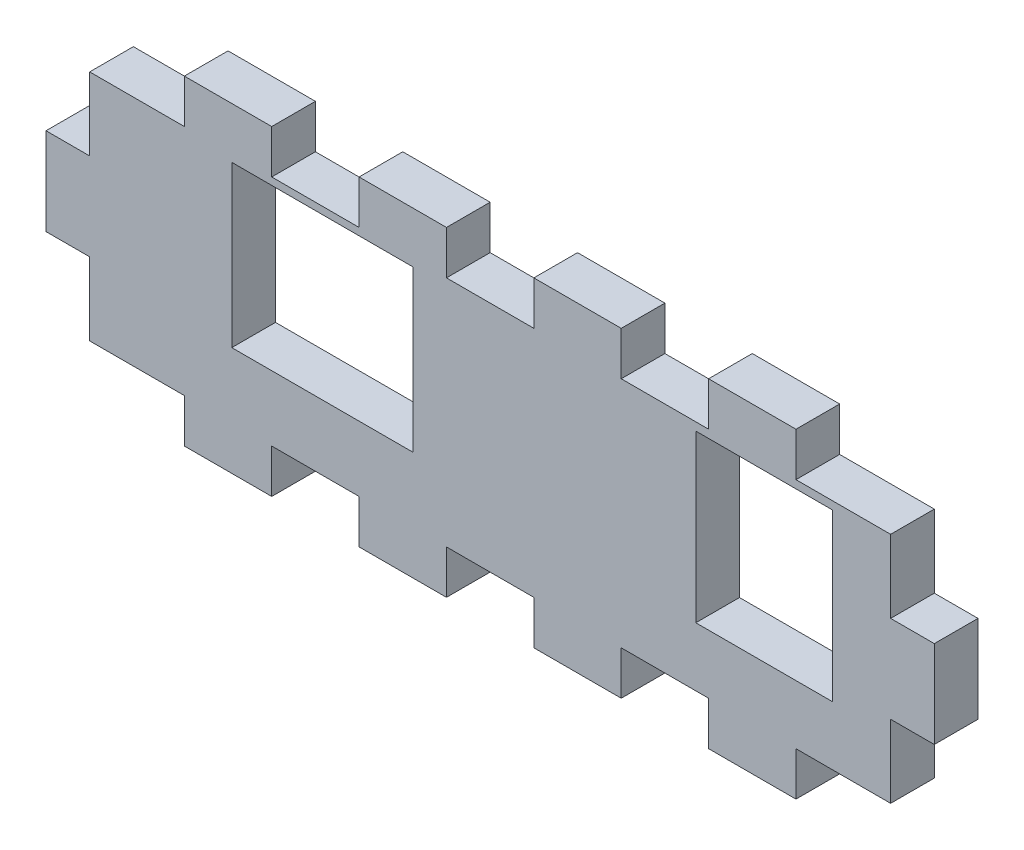
SolidWorks part; units mm, degrees
material "PMMA"
ref_plane "前视基准面" through (0, 0, 0) normal (0, 0, 1) x (1, 0, 0)
ref_plane "上视基准面" through (0, 0, 0) normal (0, 1, 0) x (1, 0, 0)
ref_plane "右视基准面" through (0, 0, 0) normal (1, 0, 0) x (0, 0, -1)
other "Configuration Table"
sketch "Model" plane through (0, 0, 0) normal (0, 0, 1) x (1, 0, 0)
  line L0 (92, 47) -> (92, 42)
  line L1 (92, 42) -> (89, 42)
  line L2 (89, 42) -> (89, 36)
  line L3 (89, 36) -> (92, 36)
  line L4 (92, 36) -> (92, 31)
  line L5 (92, 31) -> (98.5, 31)
  line L6 (98.5, 31) -> (98.5, 28)
  line L7 (98.5, 28) -> (104.5, 28)
  line L8 (104.5, 28) -> (104.5, 31)
  line L9 (104.5, 31) -> (110.5, 31)
  line L10 (110.5, 31) -> (110.5, 28)
  line L11 (110.5, 28) -> (116.5, 28)
  line L12 (116.5, 28) -> (116.5, 31)
  line L13 (116.5, 31) -> (122.5, 31)
  line L14 (122.5, 31) -> (122.5, 28)
  line L15 (122.5, 28) -> (128.5, 28)
  line L16 (128.5, 28) -> (128.5, 31)
  line L17 (128.5, 31) -> (134.5, 31)
  line L18 (134.5, 31) -> (134.5, 28)
  line L19 (134.5, 28) -> (140.5, 28)
  line L20 (140.5, 28) -> (140.5, 31)
  line L21 (140.5, 31) -> (146.5, 31)
  line L22 (146.5, 31) -> (147, 31)
  line L23 (147, 31) -> (147, 36)
  line L24 (147, 36) -> (150, 36)
  line L25 (150, 36) -> (150, 42)
  line L26 (150, 42) -> (147, 42)
  line L27 (147, 42) -> (147, 47)
  line L28 (147, 47) -> (140.5, 47)
  line L29 (140.5, 47) -> (140.5, 50)
  line L30 (140.5, 50) -> (134.5, 50)
  line L31 (134.5, 50) -> (134.5, 47)
  line L32 (134.5, 47) -> (128.5, 47)
  line L33 (128.5, 47) -> (128.5, 50)
  line L34 (128.5, 50) -> (122.5, 50)
  line L35 (122.5, 50) -> (122.5, 47)
  line L36 (122.5, 47) -> (116.5, 47)
  line L37 (116.5, 47) -> (116.5, 50)
  line L38 (116.5, 50) -> (110.5, 50)
  line L39 (110.5, 50) -> (110.5, 47)
  line L40 (110.5, 47) -> (104.5, 47)
  line L41 (104.5, 47) -> (104.5, 50)
  line L42 (104.5, 50) -> (98.5, 50)
  line L43 (98.5, 50) -> (98.5, 47)
  line L44 (98.5, 47) -> (92.5, 47)
  line L45 (92.5, 47) -> (92, 47)
extrude "凸台-拉伸1" add sketch "Model" along normal blind 3
sketch "草图2" plane through (0, 0, 3) normal (0, 0, 1) x (1, 0, 0)
  line L0 (133.622, 45.75) -> (133.622, 46.45)
  line L1 (133.622, 46.45) -> (134.322, 46.45)
  line L2 (143.022, 45.75) -> (143.022, 46.45)
  line L3 (143.022, 46.45) -> (142.322, 46.45)
  line L12 (133.822, 35.25) -> (142.822, 35.25) construction
  line L13 (133.822, 45.75) -> (133.822, 35.25) construction
  line L14 (142.822, 35.25) -> (142.822, 45.75) construction
  line L15 (142.322, 46.25) -> (134.322, 46.25) construction
  line L16 (133.822, 35.25) -> (142.822, 35.25) construction
  line L17 (133.822, 45.75) -> (133.822, 35.25) construction
  line L18 (142.822, 35.25) -> (142.822, 45.75) construction
  line L19 (142.322, 46.25) -> (134.322, 46.25) construction
  line L20 (133.622, 45.75) -> (133.622, 35.05)
  line L21 (133.622, 35.05) -> (143.022, 35.05)
  line L22 (143.022, 35.05) -> (143.022, 45.75)
  line L23 (142.322, 46.45) -> (134.322, 46.45)
  line L24 (101.957, 35.68) -> (101.957, 45.74) construction
  line L25 (113.537, 35.68) -> (102.417, 35.68) construction
  line L26 (113.997, 45.74) -> (113.997, 35.68) construction
  line L27 (113.537, 46.3) -> (102.417, 46.3) construction
  line L28 (101.957, 35.68) -> (101.957, 45.74) construction
  line L29 (113.997, 35.68) -> (101.957, 35.68) construction
  line L30 (113.997, 45.74) -> (113.997, 35.68) construction
  line L31 (113.997, 46.3) -> (101.957, 46.3) construction
  line L32 (101.957, 45.74) -> (101.957, 46.3) construction
  line L33 (113.997, 45.74) -> (113.997, 46.3) construction
  line L34 (114.197, 35.48) -> (101.757, 35.48)
  line L35 (101.757, 35.48) -> (101.757, 45.74)
  line L36 (101.757, 45.74) -> (101.757, 46.5)
  line L37 (114.197, 46.5) -> (101.757, 46.5)
  line L38 (114.197, 45.74) -> (114.197, 46.5)
  line L39 (114.197, 45.74) -> (114.197, 35.48)
  arc A0 (134.322, 46.25) -> (133.822, 45.75) centre (134.322, 45.75) ccw construction
  arc A1 (142.822, 45.75) -> (142.322, 46.25) centre (142.322, 45.75) ccw construction
  arc A2 (134.322, 46.25) -> (133.822, 45.75) centre (134.322, 45.75) ccw construction
  arc A3 (142.822, 45.75) -> (142.322, 46.25) centre (142.322, 45.75) ccw construction
  arc A6 (134.322, 46.45) -> (133.622, 45.75) centre (134.322, 45.75) ccw construction
  arc A7 (143.022, 45.75) -> (142.322, 46.45) centre (142.322, 45.75) ccw construction
  dimension "D1" = 0.2
  dimension "D2" = 0.2
extrude "切除-拉伸1" cut sketch "草图2" against normal through all
